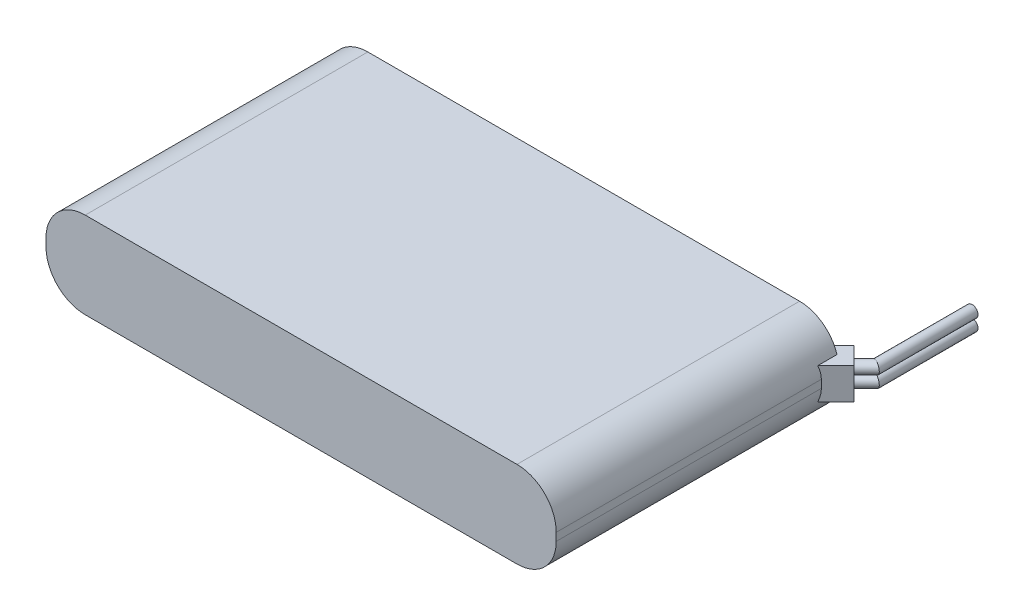
SolidWorks part; units mm, degrees
ref_plane "前视基准面" through (0, 0, 0) normal (0, 0, 1) x (1, 0, 0)
ref_plane "上视基准面" through (0, 0, 0) normal (0, 1, 0) x (1, 0, 0)
ref_plane "右视基准面" through (0, 0, 0) normal (1, 0, 0) x (0, 0, -1)
other "Configuration Table"
sketch "草图1" plane through (0, 0, 0) normal (0, 1, 0) x (1, 0, 0)
  line L1 (-62.2295, 41.1311) -> (67.7705, 41.1311)
  line L2 (-62.2295, 41.1311) -> (-62.2295, -30.8689)
  line L3 (-62.2295, -30.8689) -> (67.7705, -30.8689)
  line L4 (67.7705, 41.1311) -> (67.7705, -30.8689)
  dimension "D1" = 130
  dimension "D2" = 72
extrude "凸台-拉伸1" add sketch "草图1" along normal blind 22
fillet "圆角2" radius 10 4 edges at (67.7705, 0, -5.1311) (67.7705, 22, -5.1311) (-62.2295, 0, -5.1311) (-62.2295, 22, -5.1311)
ref_plane "基准面1" through (0, 11, 0) normal (0, -1, 0) x (-1, 0, 0)
sketch "草图2" plane through (0, 11, 0) normal (0, -1, 0) x (-1, 0, 0)
  line L0 (-62.5334, 40.3488) -> (-66.9882, 35.894)
  line L1 (-62.5334, 40.3488) -> (-67.4831, 45.2986)
  line L2 (-66.9882, 35.894) -> (-71.9379, 40.8438)
  line L3 (-67.4831, 45.2986) -> (-71.9379, 40.8438)
  line L5 (-57.7705, 41.1311) -> (-67.7705, 41.1311) construction
  line L6 (-67.4831, 45.2986) -> (-71.9379, 45.2986)
  line L7 (-71.9379, 45.2986) -> (-71.9379, 40.8438)
  dimension "D1" = 45
  dimension "D2" = 6.3
  dimension "D3" = 7
extrude "凸台-拉伸2" add sketch "草图2" along normal mid plane 8 contours L1 L3 L2 L0
ref_plane "基准面2" through (0, 12.5, 0) normal (0, 1, 0) x (1, 0, 0)
ref_plane "基准面3" through (0, 9.75, 0) normal (0, 1, 0) x (1, 0, 0)
sketch "草图66" plane through (0, 12.5, 0) normal (0, 1, 0) x (1, 0, 0)
  line L0 (69.6891, 43.0926) -> (72.4704, 45.874)
  line L1 (72.4704, 45.874) -> (72.4704, 70.4175)
  line L2 (67.4831, 45.2986) -> (71.9379, 40.8438) construction
  point P3 (69.8699, 42.9118)
  point P6 (0, 0)
  point P7 (72.4704, 70.4175)
sweep "扫描15" add path "草图66" circular profile diameter 2.95 parameters "D3"=2.95
sketch "草图68" plane through (0, 9.75, 0) normal (0, 1, 0) x (1, 0, 0)
  line L3 (-1.3907, -13.6624) -> (1.3907, -10.881)
  line L4 (1.3907, -10.881) -> (1.3907, 13.6624)
  point P8 (0, 0)
  point P9 (0, 0)
  point P10 (0, 0)
  point P11 (72.3593, 45.7126)
  point P12 (69.6137, 43.168)
  point P13 (69.473, 43.3087)
  point P14 (69.6536, 43.1281)
  point P15 (72.3452, 70.6785)
mirror "镜向1" about plane through (0, 11, 0) normal (0, -1, 0) of "扫描15"
